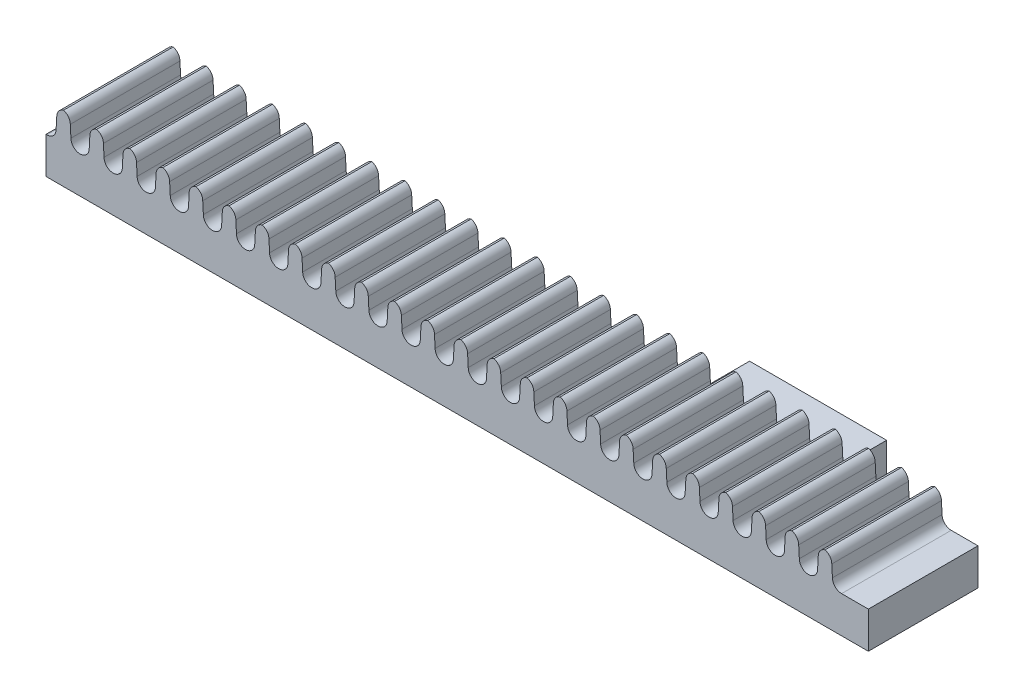
SolidWorks part; units mm, degrees
ref_plane "Front Plane" through (0, 0, 0) normal (0, 0, 1) x (1, 0, 0)
ref_plane "Top Plane" through (0, 0, 0) normal (0, 1, 0) x (1, 0, 0)
ref_plane "Right Plane" through (0, 0, 0) normal (1, 0, 0) x (0, 0, -1)
sketch "Sketch1" plane through (0, 0, 0) normal (0, 1, 0) x (1, 0, 0)
  line L0 (75, 12) -> (90, 12)
  line L1 (0, 0) -> (90, 0)
  line L2 (0, 0) -> (0, 12)
  line L3 (0, 12) -> (60, 12)
  line L4 (90, 0) -> (90, 12)
  line L6 (60, 12) -> (60, 17)
  line L7 (60, 17) -> (75, 17)
  line L8 (75, 12) -> (75, 17)
  dimension "D1" = 12
  dimension "D2" = 90
  dimension "D3" = 60
  dimension "D4" = 15
  dimension "D5" = 5
extrude "Boss-Extrude1" add sketch "Sketch1" along normal blind 4
sketch "Sketch2" plane through (0, 0, 0) normal (0, 0, 1) x (1, 0, 0)
  line L0 (87.0683, 4) -> (87.0683, 3.0713) construction
  line L3 (1.1051, 5) -> (1.1756, 6.2726)
  line L8 (0, 4) -> (90, 4) construction
  line L9 (1.9168, 8.3601) -> (1.9168, 4.1118) construction
  line L10 (4.7285, 5) -> (4.7991, 6.2726)
  line L11 (2.7285, 5) -> (2.658, 6.2726)
  line L12 (5.5403, 7.2385) -> (5.5403, 2.8054) construction
  line L13 (8.352, 5) -> (8.4225, 6.2726)
  line L14 (6.352, 5) -> (6.2814, 6.2726)
  line L15 (11.9755, 5) -> (12.046, 6.2726)
  line L16 (9.9755, 5) -> (9.9049, 6.2726)
  line L17 (12.7872, 7.2385) -> (12.7872, 3.5075) construction
  line L18 (20.0341, 7.2385) -> (20.0341, 2.8054) construction
  line L19 (23.6576, 8.3601) -> (23.6576, 4.1118) construction
  line L20 (15.5989, 5) -> (15.6695, 6.2726)
  line L21 (13.5989, 5) -> (13.5284, 6.2726)
  line L22 (19.2224, 5) -> (19.2929, 6.2726)
  line L23 (17.2224, 5) -> (17.1518, 6.2726)
  line L24 (22.8459, 5) -> (22.9164, 6.2726)
  line L25 (20.8459, 5) -> (20.7753, 6.2726)
  line L26 (26.4693, 5) -> (26.5399, 6.2726)
  line L27 (24.4693, 5) -> (24.3988, 6.2726)
  line L28 (27.2811, 7.2385) -> (27.2811, 2.3137) construction
  line L29 (30.9045, 8.3601) -> (30.9045, 4.1118) construction
  line L30 (34.528, 7.2385) -> (34.528, 2.8054) construction
  line L31 (41.7749, 7.2385) -> (41.7749, 3.5075) construction
  line L32 (49.0219, 7.2385) -> (49.0219, 2.8054) construction
  line L33 (52.6453, 8.3601) -> (52.6453, 4.1118) construction
  line L34 (30.0928, 5) -> (30.1633, 6.2726)
  line L35 (28.0928, 5) -> (28.0222, 6.2726)
  line L36 (33.7163, 5) -> (33.7868, 6.2726)
  line L37 (31.7163, 5) -> (31.6457, 6.2726)
  line L38 (37.3397, 5) -> (37.4103, 6.2726)
  line L39 (35.3397, 5) -> (35.2692, 6.2726)
  line L40 (40.9632, 5) -> (41.0337, 6.2726)
  line L41 (38.9632, 5) -> (38.8926, 6.2726)
  line L42 (44.5867, 5) -> (44.6572, 6.2726)
  line L43 (42.5867, 5) -> (42.5161, 6.2726)
  line L44 (48.2101, 5) -> (48.2807, 6.2726)
  line L45 (46.2101, 5) -> (46.1396, 6.2726)
  line L46 (51.8336, 5) -> (51.9041, 6.2726)
  line L47 (49.8336, 5) -> (49.763, 6.2726)
  line L48 (55.4571, 5) -> (55.5276, 6.2726)
  line L49 (53.4571, 5) -> (53.3865, 6.2726)
  line L50 (56.2688, 7.2385) -> (56.2688, 2.518) construction
  line L51 (59.8923, 8.3601) -> (59.8923, 4.1118) construction
  line L52 (63.5157, 7.2385) -> (63.5157, 2.8054) construction
  line L53 (70.7627, 7.2385) -> (70.7627, 3.5075) construction
  line L54 (78.0096, 7.2385) -> (78.0096, 2.8054) construction
  line L55 (81.6331, 8.3601) -> (81.6331, 4.1118) construction
  line L56 (85.2565, 7.2385) -> (85.2565, 2.3137) construction
  line L57 (87.0683, 4) -> (87.0683, 1.9023)
  line L58 (87.0683, 1.9023) -> (0.1051, 2.3137)
  line L59 (0.1051, 2.3137) -> (0.1051, 4)
  line L60 (59.0805, 5) -> (59.1511, 6.2726)
  line L61 (57.0805, 5) -> (57.01, 6.2726)
  line L62 (62.704, 5) -> (62.7745, 6.2726)
  line L63 (60.704, 5) -> (60.6334, 6.2726)
  line L64 (66.3275, 5) -> (66.398, 6.2726)
  line L65 (64.3275, 5) -> (64.2569, 6.2726)
  line L66 (69.9509, 5) -> (70.0215, 6.2726)
  line L67 (67.9509, 5) -> (67.8804, 6.2726)
  line L68 (73.5744, 5) -> (73.6449, 6.2726)
  line L69 (71.5744, 5) -> (71.5038, 6.2726)
  line L70 (77.1979, 5) -> (77.2684, 6.2726)
  line L71 (75.1979, 5) -> (75.1273, 6.2726)
  line L72 (80.8213, 5) -> (80.8919, 6.2726)
  line L73 (78.8213, 5) -> (78.7508, 6.2726)
  line L74 (84.4448, 5) -> (84.5153, 6.2726)
  line L75 (82.4448, 5) -> (82.3742, 6.2726)
  line L77 (86.0683, 5) -> (85.9977, 6.2726)
  arc A0 (0.1051, 4) -> (1.1051, 5) centre (0.1051, 5) ccw
  arc A1 (1.9168, 7.2385) -> (1.1756, 6.2726) centre (2.1756, 6.2726) ccw
  arc A3 (5.5403, 7.2385) -> (4.7991, 6.2726) centre (5.7991, 6.2726) ccw
  arc A4 (1.9168, 7.2385) -> (2.658, 6.2726) centre (1.658, 6.2726) cw
  arc A5 (4.7285, 5) -> (2.7285, 5) centre (3.7285, 5) cw
  arc A6 (6.352, 5) -> (8.352, 5) centre (7.352, 5) ccw
  arc A7 (9.1637, 7.2385) -> (8.4225, 6.2726) centre (9.4225, 6.2726) ccw
  arc A8 (5.5403, 7.2385) -> (6.2814, 6.2726) centre (5.2814, 6.2726) cw
  arc A9 (12.7872, 7.2385) -> (12.046, 6.2726) centre (13.046, 6.2726) ccw
  arc A10 (9.1637, 7.2385) -> (9.9049, 6.2726) centre (8.9049, 6.2726) cw
  arc A11 (11.9755, 5) -> (9.9755, 5) centre (10.9755, 5) cw
  arc A12 (13.5989, 5) -> (15.5989, 5) centre (14.5989, 5) ccw
  arc A13 (16.4107, 7.2385) -> (15.6695, 6.2726) centre (16.6695, 6.2726) ccw
  arc A14 (12.7872, 7.2385) -> (13.5284, 6.2726) centre (12.5284, 6.2726) cw
  arc A15 (20.0341, 7.2385) -> (19.2929, 6.2726) centre (20.2929, 6.2726) ccw
  arc A16 (16.4107, 7.2385) -> (17.1518, 6.2726) centre (16.1518, 6.2726) cw
  arc A17 (19.2224, 5) -> (17.2224, 5) centre (18.2224, 5) cw
  arc A18 (20.8459, 5) -> (22.8459, 5) centre (21.8459, 5) ccw
  arc A19 (23.6576, 7.2385) -> (22.9164, 6.2726) centre (23.9164, 6.2726) ccw
  arc A20 (20.0341, 7.2385) -> (20.7753, 6.2726) centre (19.7753, 6.2726) cw
  arc A21 (27.2811, 7.2385) -> (26.5399, 6.2726) centre (27.5399, 6.2726) ccw
  arc A22 (23.6576, 7.2385) -> (24.3988, 6.2726) centre (23.3988, 6.2726) cw
  arc A23 (26.4693, 5) -> (24.4693, 5) centre (25.4693, 5) cw
  arc A24 (28.0928, 5) -> (30.0928, 5) centre (29.0928, 5) ccw
  arc A25 (30.9045, 7.2385) -> (30.1633, 6.2726) centre (31.1633, 6.2726) ccw
  arc A26 (27.2811, 7.2385) -> (28.0222, 6.2726) centre (27.0222, 6.2726) cw
  arc A27 (34.528, 7.2385) -> (33.7868, 6.2726) centre (34.7868, 6.2726) ccw
  arc A28 (30.9045, 7.2385) -> (31.6457, 6.2726) centre (30.6457, 6.2726) cw
  arc A29 (33.7163, 5) -> (31.7163, 5) centre (32.7163, 5) cw
  arc A30 (35.3397, 5) -> (37.3397, 5) centre (36.3397, 5) ccw
  arc A31 (38.1515, 7.2385) -> (37.4103, 6.2726) centre (38.4103, 6.2726) ccw
  arc A32 (34.528, 7.2385) -> (35.2692, 6.2726) centre (34.2692, 6.2726) cw
  arc A33 (41.7749, 7.2385) -> (41.0337, 6.2726) centre (42.0337, 6.2726) ccw
  arc A34 (38.1515, 7.2385) -> (38.8926, 6.2726) centre (37.8926, 6.2726) cw
  arc A35 (40.9632, 5) -> (38.9632, 5) centre (39.9632, 5) cw
  arc A36 (42.5867, 5) -> (44.5867, 5) centre (43.5867, 5) ccw
  arc A37 (45.3984, 7.2385) -> (44.6572, 6.2726) centre (45.6572, 6.2726) ccw
  arc A38 (41.7749, 7.2385) -> (42.5161, 6.2726) centre (41.5161, 6.2726) cw
  arc A39 (49.0219, 7.2385) -> (48.2807, 6.2726) centre (49.2807, 6.2726) ccw
  arc A40 (45.3984, 7.2385) -> (46.1396, 6.2726) centre (45.1396, 6.2726) cw
  arc A41 (48.2101, 5) -> (46.2101, 5) centre (47.2101, 5) cw
  arc A42 (49.8336, 5) -> (51.8336, 5) centre (50.8336, 5) ccw
  arc A43 (52.6453, 7.2385) -> (51.9041, 6.2726) centre (52.9041, 6.2726) ccw
  arc A44 (49.0219, 7.2385) -> (49.763, 6.2726) centre (48.763, 6.2726) cw
  arc A45 (56.2688, 7.2385) -> (55.5276, 6.2726) centre (56.5276, 6.2726) ccw
  arc A46 (52.6453, 7.2385) -> (53.3865, 6.2726) centre (52.3865, 6.2726) cw
  arc A47 (55.4571, 5) -> (53.4571, 5) centre (54.4571, 5) cw
  arc A48 (57.0805, 5) -> (59.0805, 5) centre (58.0805, 5) ccw
  arc A49 (59.8923, 7.2385) -> (59.1511, 6.2726) centre (60.1511, 6.2726) ccw
  arc A50 (56.2688, 7.2385) -> (57.01, 6.2726) centre (56.01, 6.2726) cw
  arc A51 (63.5157, 7.2385) -> (62.7745, 6.2726) centre (63.7745, 6.2726) ccw
  arc A52 (59.8923, 7.2385) -> (60.6334, 6.2726) centre (59.6334, 6.2726) cw
  arc A53 (62.704, 5) -> (60.704, 5) centre (61.704, 5) cw
  arc A54 (64.3275, 5) -> (66.3275, 5) centre (65.3275, 5) ccw
  arc A55 (67.1392, 7.2385) -> (66.398, 6.2726) centre (67.398, 6.2726) ccw
  arc A56 (63.5157, 7.2385) -> (64.2569, 6.2726) centre (63.2569, 6.2726) cw
  arc A57 (70.7627, 7.2385) -> (70.0215, 6.2726) centre (71.0215, 6.2726) ccw
  arc A58 (67.1392, 7.2385) -> (67.8804, 6.2726) centre (66.8804, 6.2726) cw
  arc A59 (69.9509, 5) -> (67.9509, 5) centre (68.9509, 5) cw
  arc A60 (71.5744, 5) -> (73.5744, 5) centre (72.5744, 5) ccw
  arc A61 (74.3861, 7.2385) -> (73.6449, 6.2726) centre (74.6449, 6.2726) ccw
  arc A62 (70.7627, 7.2385) -> (71.5038, 6.2726) centre (70.5038, 6.2726) cw
  arc A63 (78.0096, 7.2385) -> (77.2684, 6.2726) centre (78.2684, 6.2726) ccw
  arc A64 (74.3861, 7.2385) -> (75.1273, 6.2726) centre (74.1273, 6.2726) cw
  arc A65 (77.1979, 5) -> (75.1979, 5) centre (76.1979, 5) cw
  arc A66 (78.8213, 5) -> (80.8213, 5) centre (79.8213, 5) ccw
  arc A67 (81.6331, 7.2385) -> (80.8919, 6.2726) centre (81.8919, 6.2726) ccw
  arc A68 (78.0096, 7.2385) -> (78.7508, 6.2726) centre (77.7508, 6.2726) cw
  arc A69 (85.2565, 7.2385) -> (84.5153, 6.2726) centre (85.5153, 6.2726) ccw
  arc A70 (81.6331, 7.2385) -> (82.3742, 6.2726) centre (81.3742, 6.2726) cw
  arc A71 (84.4448, 5) -> (82.4448, 5) centre (83.4448, 5) cw
  arc A72 (86.0683, 5) -> (87.0683, 4) centre (87.0683, 5) ccw
  arc A74 (85.2565, 7.2385) -> (85.9977, 6.2726) centre (84.9977, 6.2726) cw
  point P16 (0.1051, 4)
  point P24 (3.7285, 4)
  point P42 (7.352, 4)
  point P43 (10.9755, 4)
  point P80 (14.5989, 4)
  point P81 (18.2224, 4)
  point P82 (21.8459, 4)
  point P83 (25.4693, 4)
  point P156 (29.0928, 4)
  point P157 (32.7163, 4)
  point P158 (36.3397, 4)
  point P159 (39.9632, 4)
  point P160 (43.5867, 4)
  point P161 (47.2101, 4)
  point P162 (50.8336, 4)
  point P163 (54.4571, 4)
  point P275 (58.0805, 4)
  point P276 (61.704, 4)
  point P277 (65.3275, 4)
  point P278 (68.9509, 4)
  point P279 (72.5744, 4)
  point P280 (76.1979, 4)
  point P281 (79.8213, 4)
  point P282 (83.4448, 4)
  point P283 (87.0683, 4)
  dimension "D2" = 2
  dimension "D3" = 2
  dimension "D5" = 1
  dimension "D1" = 3.2385
  dimension "D7" = 1.2726
extrude "Boss-Extrude3" add sketch "Sketch2" against normal blind 12
